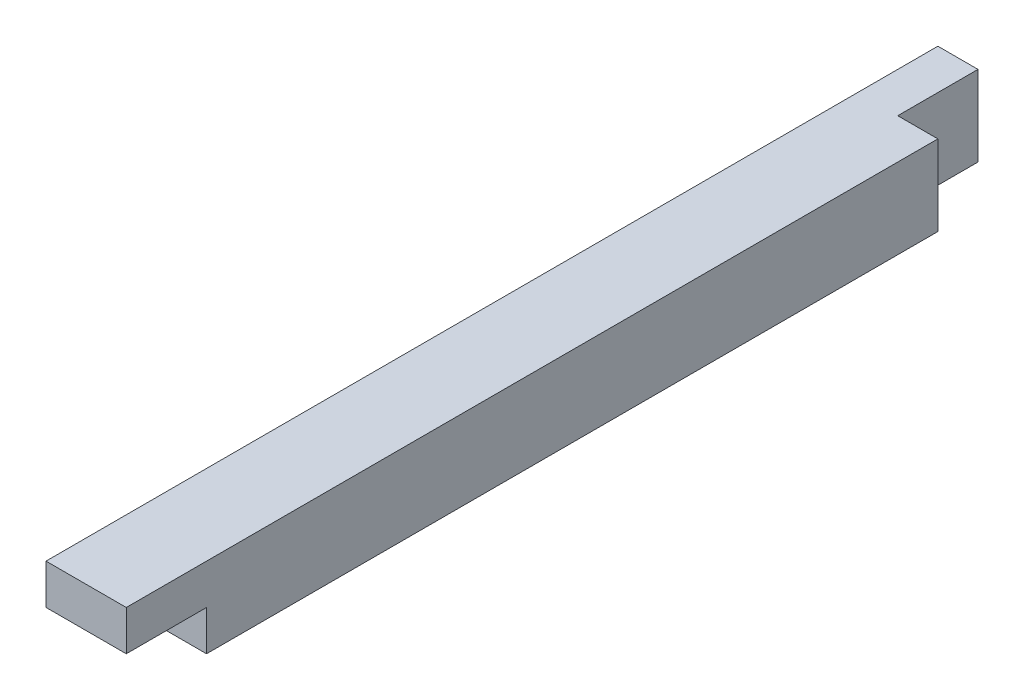
SolidWorks part; units mm, degrees
ref_plane "Front Plane" through (0, 0, 0) normal (0, 0, 1) x (1, 0, 0)
ref_plane "Top Plane" through (0, 0, 0) normal (0, 1, 0) x (1, 0, 0)
ref_plane "Right Plane" through (0, 0, 0) normal (1, 0, 0) x (0, 0, -1)
sketch "Sketch1" plane through (0, 0, 0) normal (0, 0, 1) x (1, 0, 0)
  line L1 (0, 0) -> (90, 0)
  line L2 (0, 0) -> (0, 90)
  line L3 (0, 90) -> (90, 90)
  line L4 (90, 0) -> (90, 90)
  dimension "D1" = 90
  dimension "D2" = 90
extrude "Boss-Extrude1" add sketch "Sketch1" along normal blind 1000
sketch "Sketch3" plane through (0, 0, 0) normal (0, -1, 0) x (1, 0, 0)
  line L0 (90, 1000) -> (90, 0) construction
  line L1 (0, 1000) -> (90, 1000)
  line L2 (0, 1000) -> (0, 910)
  line L3 (0, 910) -> (90, 910)
  line L4 (90, 1000) -> (90, 910)
  dimension "D1" = 90
extrude "Cut-Extrude1" cut sketch "Sketch3" against normal blind 45
sketch "Sketch4" plane through (90, 0, 0) normal (1, 0, 0) x (0, 0, -1)
  line L0 (-910, 0) -> (0, 0) construction
  line L1 (0, 90) -> (-90, 90)
  line L2 (0, 90) -> (0, 0)
  line L3 (0, 0) -> (-90, 0)
  line L4 (-90, 90) -> (-90, 0)
  dimension "D1" = 90
extrude "Cut-Extrude2" cut sketch "Sketch4" against normal blind 45
